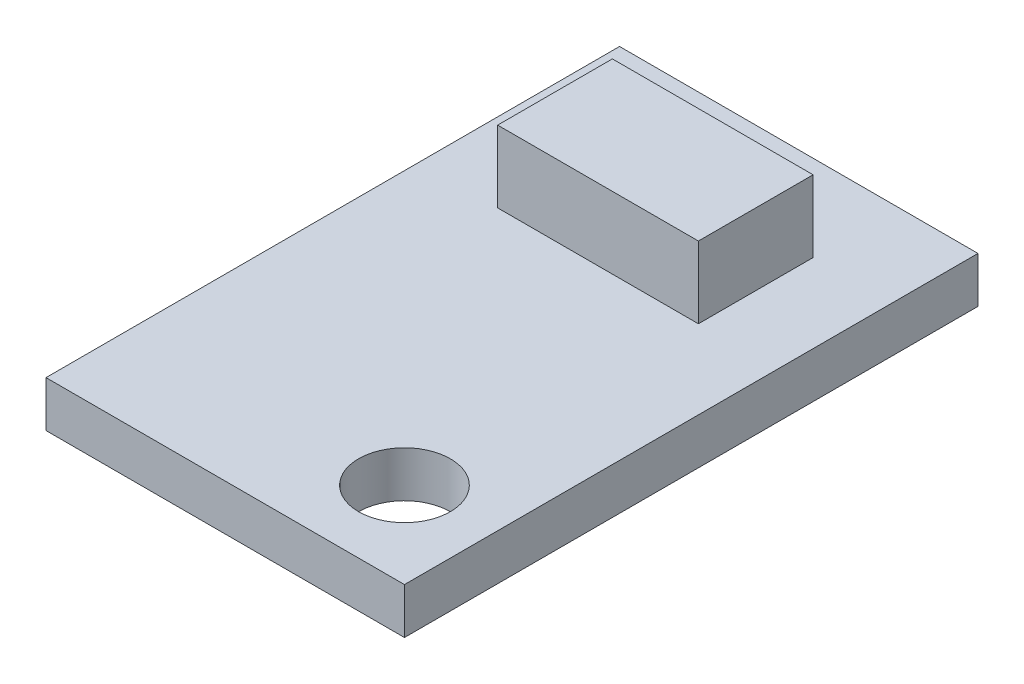
SolidWorks part; units mm, degrees
ref_plane "Front Plane" through (0, 0, 0) normal (0, 0, 1) x (1, 0, 0)
ref_plane "Top Plane" through (0, 0, 0) normal (0, 1, 0) x (1, 0, 0)
ref_plane "Right Plane" through (0, 0, 0) normal (1, 0, 0) x (0, 0, -1)
sketch "Sketch1" plane through (0, 0, 0) normal (0, 1, 0) x (1, 0, 0)
  line L1 (-6.25, 0) -> (6.25, 0)
  line L2 (-6.25, 0) -> (-6.25, 20)
  line L3 (-6.25, 20) -> (6.25, 20)
  line L4 (6.25, 0) -> (6.25, 20)
  circle A0 centre (3.25, 3) radius 1.6
  dimension "D3" = 3.2
  dimension "D1" = 12.5
  dimension "D2" = 20
  dimension "D4" = 3
  dimension "D5" = 3
extrude "Boss-Extrude1" add sketch "Sketch1" along normal blind 1.6
sketch "Sketch2" plane through (0, 1.6, 0) normal (0, 1, 0) x (1, 0, 0)
  line L0 (0, 0) -> (0, 50000) construction
  line L1 (-3.5, 17) -> (3.5, 17)
  line L2 (-3.5, 17) -> (-3.5, 13)
  line L3 (-3.5, 13) -> (3.5, 13)
  line L4 (3.5, 17) -> (3.5, 13)
  line L5 (-6.25, 0) -> (6.25, 0) construction
  line L6 (6.25, 20) -> (-6.25, 20) construction
  point P8 (0, 0)
  dimension "D1" = 7
  dimension "D2" = 4
  dimension "D3" = 3
extrude "Boss-Extrude2" add sketch "Sketch2" along normal blind 2.5
